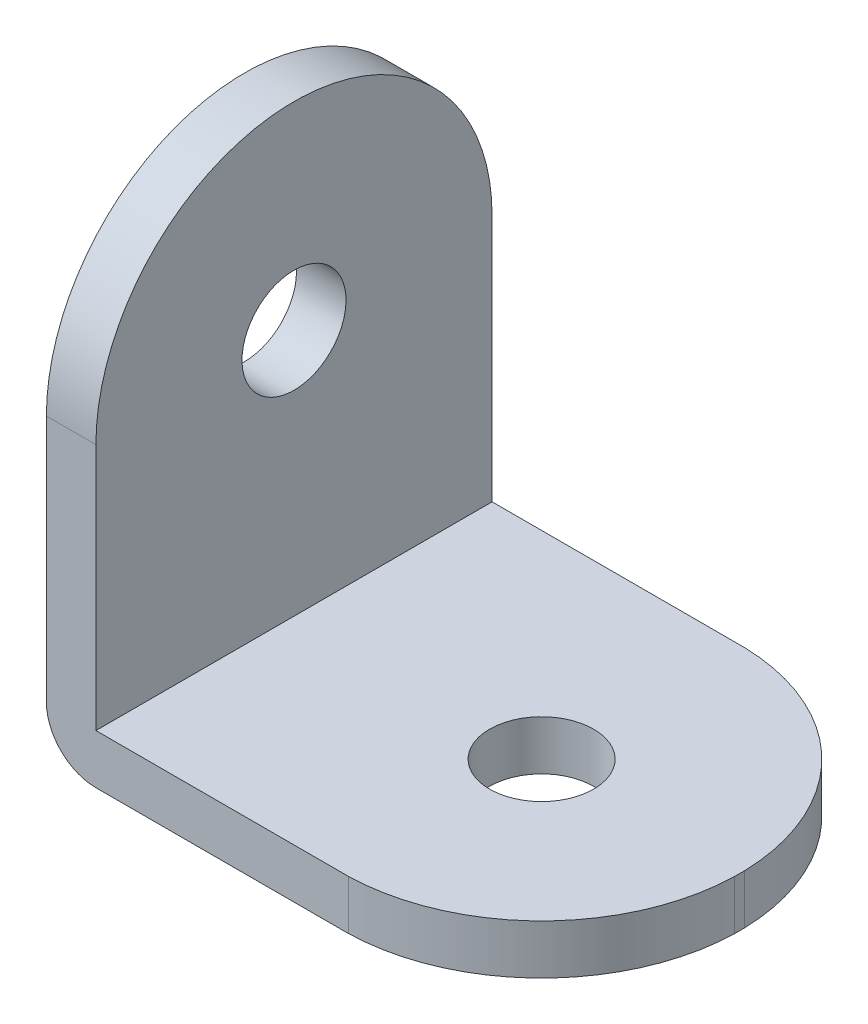
SolidWorks part; units mm, degrees
ref_plane "前视基准面" through (0, 0, 0) normal (0, 0, 1) x (1, 0, 0)
ref_plane "上视基准面" through (0, 0, 0) normal (0, 1, 0) x (1, 0, 0)
ref_plane "右视基准面" through (0, 0, 0) normal (1, 0, 0) x (0, 0, -1)
other "Configuration Table"
sketch "草图1" plane through (0, 0, 0) normal (0, 0, 1) x (1, 0, 0)
  line L1 (10, -10) -> (-10, -10)
  line L2 (10, -10) -> (10, 10)
  line L3 (10, 10) -> (-10, 10)
  line L4 (-10, -10) -> (-10, 10)
  line L5 (10, -10) -> (-10, 10) construction
  line L6 (10, 10) -> (-10, -10) construction
  point P0 (0, 0)
  dimension "D1" = 20
  dimension "D2" = 20
extrude "凸台-拉伸1" add sketch "草图1" along normal blind 16
sketch "草图2" plane through (0, 0, 16) normal (0, 0, 1) x (1, 0, 0)
  line L0 (-8, 10) -> (-8, -8)
  line L1 (10, 10) -> (-10, 10) construction
  line L2 (-8, -8) -> (10, -8)
  line L3 (10, -10) -> (10, 10) construction
  line L4 (10, -8) -> (10, 10)
  line L5 (10, 10) -> (-8, 10)
  line L6 (-10, 10) -> (-10, -10) construction
  line L7 (-10, -10) -> (10, -10) construction
  dimension "D1" = 2
  dimension "D2" = 2
extrude "切除-拉伸1" cut sketch "草图2" against normal blind 16
sketch "草图3" plane through (-8, 0, 0) normal (1, 0, 0) x (0, 0, -1)
  line L0 (-16, 10) -> (-16, 2)
  line L1 (-16, 10) -> (-16, -8) construction
  circle A0 centre (-8, 2) radius 2.1
  dimension "D1" = 8
extrude "切除-拉伸2" cut sketch "草图3" against normal blind 16 contours A0
sketch "草图4" plane through (0, -8, 0) normal (0, 1, 0) x (1, 0, 0)
  line L0 (10, 0) -> (2, 0)
  line L1 (-8, 0) -> (10, 0) construction
  circle A0 centre (2, -8) radius 2.1
  dimension "D1" = 8
extrude "切除-拉伸3" cut sketch "草图4" against normal blind 16 contours A0
sketch "草图5" plane through (-8, 0, 0) normal (1, 0, 0) x (0, 0, -1)
  line L0 (-16, 10) -> (-16, -8) construction
  line L1 (0, 10) -> (0, -8) construction
  line L2 (-16, 2) -> (-16, 10)
  line L3 (-16, 10) -> (0, 10)
  line L4 (0, 10) -> (0, 2)
  arc A0 (-16, 2) -> (0, 2) centre (-8, 2) cw
  line M2 (-16, 10) -> (-16, -8)
  line M4 (0, -8) -> (0, 10)
  line M5 (0, 10) -> (-16, 10)
extrude "切除-拉伸4" cut sketch "草图5" against normal blind 16 contours A0 L3 M2 | A0 M5 M4
sketch "草图6" plane through (0, -8, 0) normal (0, 1, 0) x (1, 0, 0)
  line L1 (-8, -16) -> (10, -16) construction
  line L2 (2, 0.0025) -> (10, 0)
  line L3 (10, 0) -> (10, -16)
  line L4 (10, -16) -> (2.2012, -16)
  arc A0 (2.2012, -16) -> (2, 0.0025) centre (2, -8) ccw
  line M2 (-8, -16) -> (10, -16)
  line M3 (10, -16) -> (10, 0)
  line M4 (10, 0) -> (-8, 0)
extrude "切除-拉伸5" cut sketch "草图6" against normal blind 16 contours A0 M3 M4 | A0 M2 M3
sketch "草图7" plane through (0, 0, 16) normal (0, 0, 1) x (1, 0, 0)
  line L0 (-10, 2) -> (-10, -10) construction
  line L1 (-10, -10) -> (2.2012, -10) construction
  line L2 (-10, -8) -> (-10, -10)
  line L3 (-10, -10) -> (-8, -10)
  arc A0 (-10, -8) -> (-8, -10) centre (-8, -8) ccw
extrude "切除-拉伸6" cut sketch "草图7" against normal blind 16
equation "\"16】\"=10"
